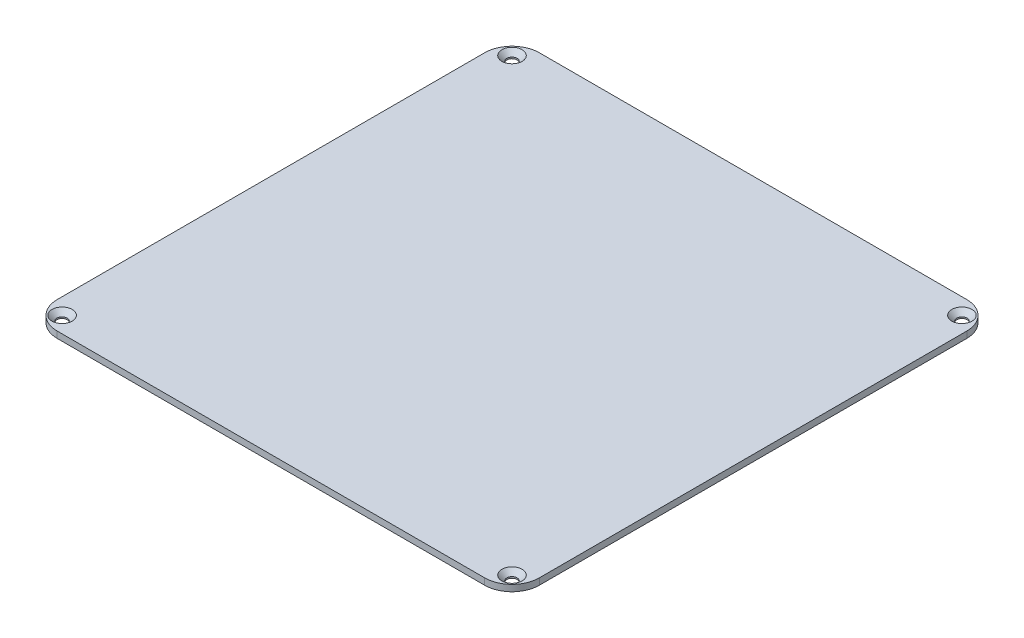
SolidWorks part; units mm, degrees
ref_plane "Ebene vorne" through (0, 0, 0) normal (0, 0, 1) x (1, 0, 0)
ref_plane "Ebene oben" through (0, 0, 0) normal (0, 1, 0) x (1, 0, 0)
ref_plane "Ebene rechts" through (0, 0, 0) normal (1, 0, 0) x (0, 0, -1)
sketch "Skizze1" plane through (0, 0, 0) normal (0, 1, 0) x (1, 0, 0)
  line L1 (0, 0) -> (300, 0)
  line L2 (0, 0) -> (0, 300)
  line L3 (0, 300) -> (300, 300)
  line L4 (300, 0) -> (300, 300)
  dimension "D1" = 300
extrude "Aufsatz-Linear austragen1" add sketch "Skizze1" along normal blind 4
fillet "Verrundung1" radius 17 4 edges at (0, 2, -300) (300, 2, -300) (300, 2, 0) (0, 2, 0)
hole_wizard "Formsenkung für M6 Senkschraube mit Schlitz/Kreuzschlitz1" positions "Skizze3" profile "Skizze2" countersink size "M6" standard "DIN" end condition through all
sketch "Skizze3" plane through (0, 4, 0) normal (0, 1, 0) x (1, 0, 0)
  line L0 (0, 283) -> (0, 17) construction
  line L1 (17, 0) -> (283, 0) construction
  line L2 (283, 300) -> (17, 300) construction
  line L3 (300, 17) -> (300, 283) construction
  point P0 (290, 10)
  point P2 (10, 10)
  point P4 (10, 290)
  point P6 (290, 290)
  dimension "D1" = 10
  dimension "D2" = 10
  dimension "D3" = 10
  dimension "D4" = 10
sketch "Skizze2" plane through (290, 4, -10) normal (1, 0, 0) x (0, 0, 1)
  line L0 (0, 0) -> (0, 4)
  line L1 (0, 4) -> (3.2, 4)
  line L2 (3.2, 4) -> (3.2, 3.1)
  line L3 (3.2, 3.1) -> (6.3, 0)
  line L5 (6.3, 0) -> (0, 0)
  line L6 (-3.2, 3.1) -> (-6.3, 0) construction
  line L11 (0, -6.35) -> (0, 107.95) construction
  dimension "Bohrerdurchmesser" = 6.4
  dimension "Bohrungstiefe" = 4
  dimension "Senkdurchmesser (Oben)" = 12.6
  dimension "Senkwinkel (Oben)" = 90
